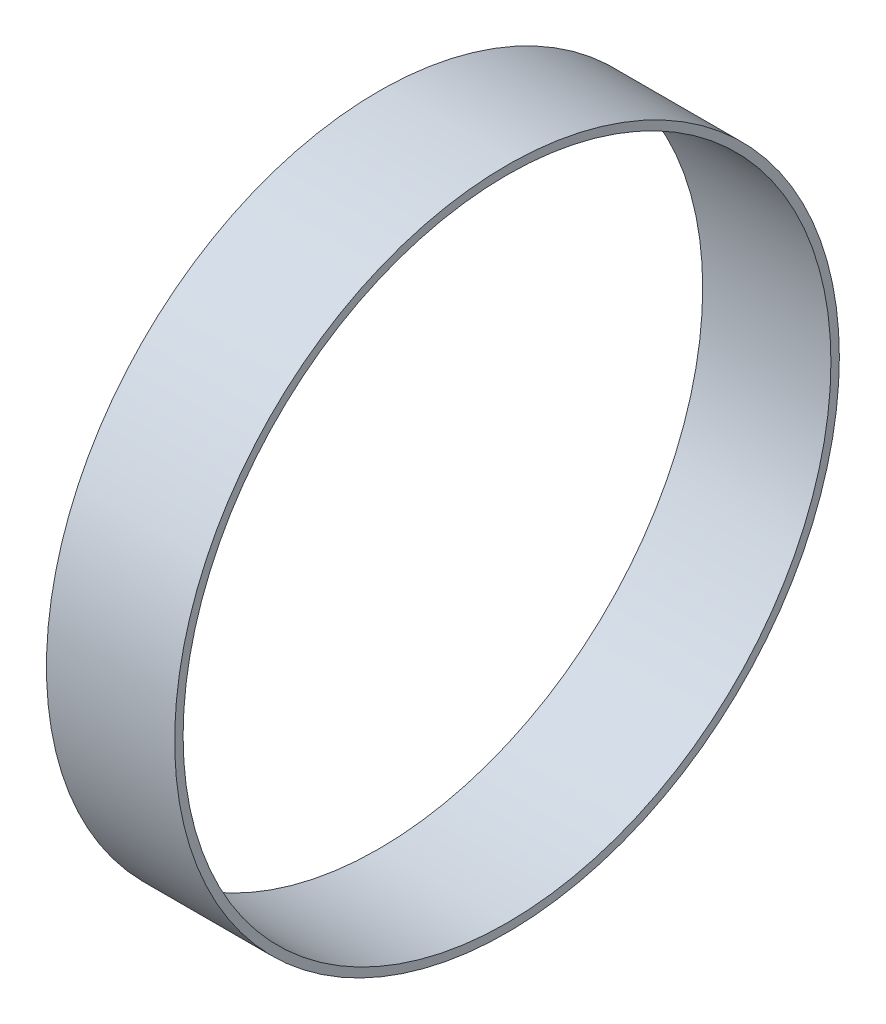
SolidWorks part; units mm, degrees
ref_plane "Front Plane" through (0, 0, 0) normal (0, 0, 1) x (1, 0, 0)
ref_plane "Top Plane" through (0, 0, 0) normal (0, 1, 0) x (1, 0, 0)
ref_plane "Right Plane" through (0, 0, 0) normal (1, 0, 0) x (0, 0, -1)
sketch "Sketch1" plane through (0, 0, 0) normal (1, 0, 0) x (0, 0, -1)
  circle A0 centre (0, 0) radius 98.5
  circle A1 centre (0, 0) radius 96
  dimension "D1" = 192
  dimension "D2" = 197
extrude "Boss-Extrude1" add sketch "Sketch1" along normal blind 38
